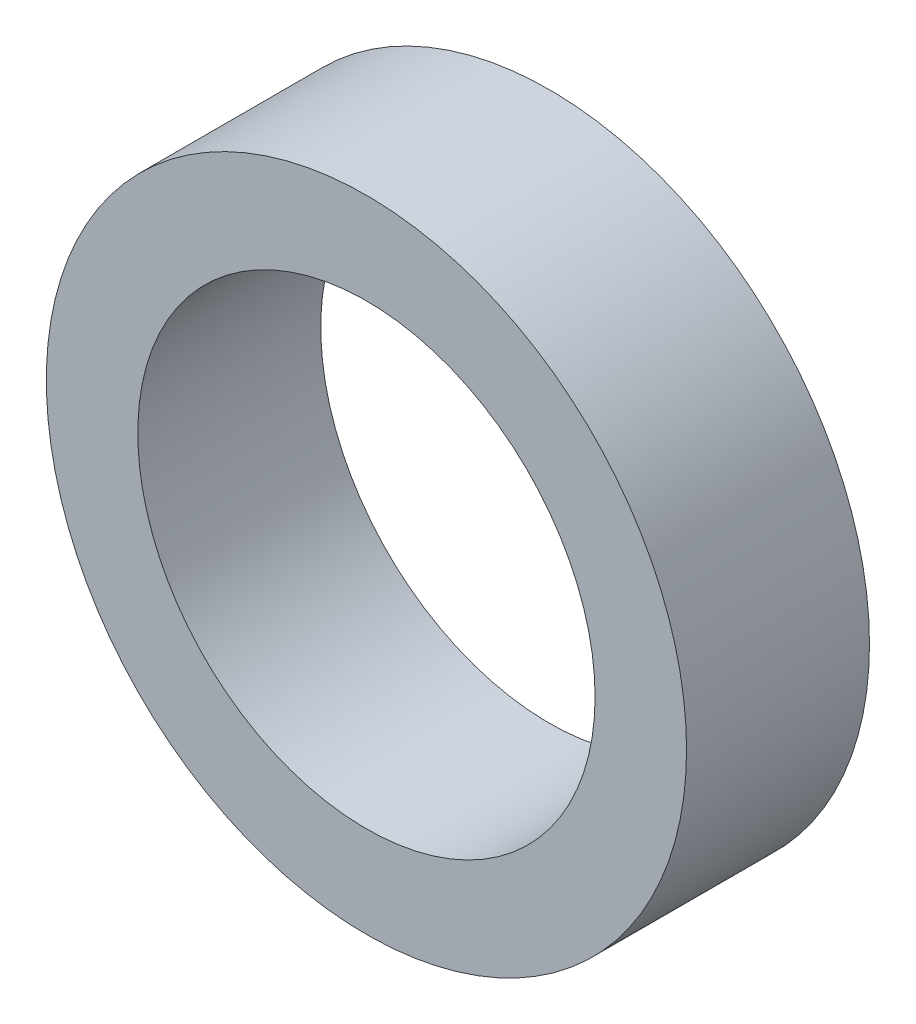
SolidWorks part; units mm, degrees
ref_plane "Front Plane" through (0, 0, 0) normal (0, 0, 1) x (1, 0, 0)
ref_plane "Top Plane" through (0, 0, 0) normal (0, 1, 0) x (1, 0, 0)
ref_plane "Right Plane" through (0, 0, 0) normal (1, 0, 0) x (0, 0, -1)
sketch "Sketch1" plane through (0, 0, 0) normal (0, 0, 1) x (1, 0, 0)
  circle A0 centre (0, 0) radius 63.5
  circle A1 centre (0, 0) radius 88.9
  dimension "D1" = 127
  dimension "D2" = 177.8
extrude "Boss-Extrude1" add sketch "Sketch1" along normal mid plane 50.8
